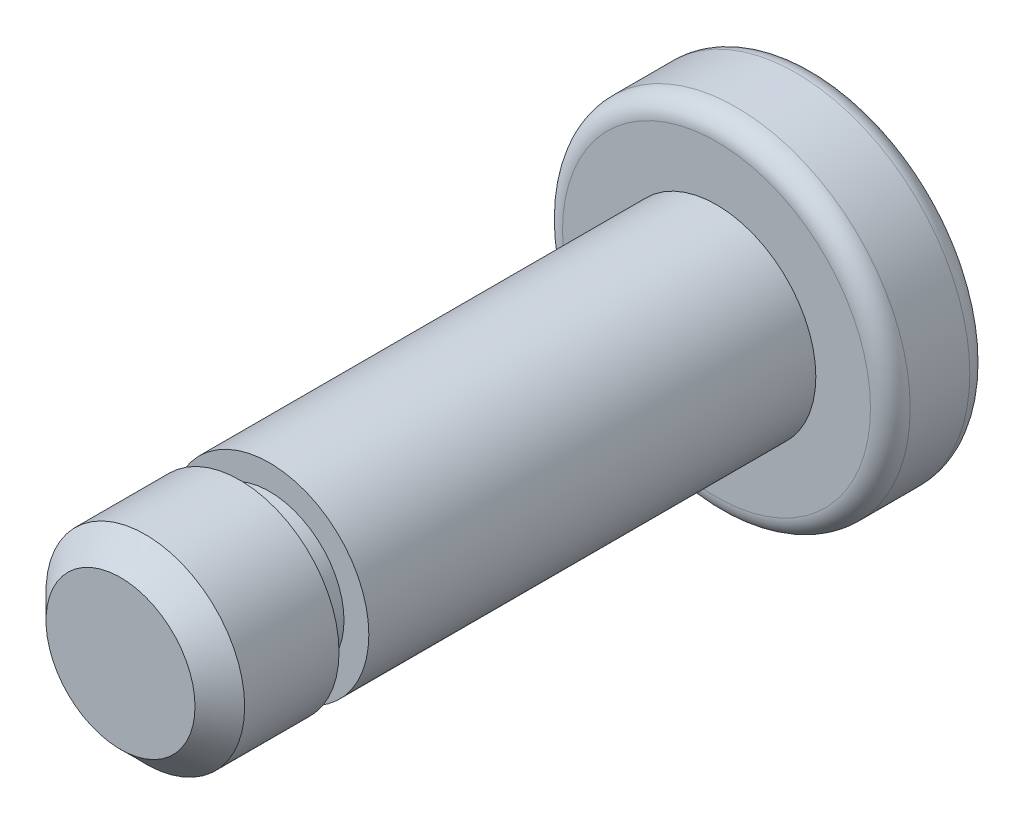
SolidWorks part; units mm, degrees
ref_plane "前视基准面" through (0, 0, 0) normal (0, 0, 1) x (1, 0, 0)
ref_plane "上视基准面" through (0, 0, 0) normal (0, 1, 0) x (1, 0, 0)
ref_plane "右视基准面" through (0, 0, 0) normal (1, 0, 0) x (0, 0, -1)
sketch "草图1" plane through (0, 0, 0) normal (0, 0, 1) x (1, 0, 0)
  circle A0 centre (0, 0) radius 3.5
  dimension "D1" = 7
extrude "凸台-拉伸1" add sketch "草图1" along normal blind 2
sketch "草图2" plane through (0, 0, 2) normal (0, 0, 1) x (1, 0, 0)
  circle A0 centre (0, 0) radius 2
  dimension "D1" = 4
extrude "凸台-拉伸2" add sketch "草图2" along normal blind 12
sketch "草图3" plane through (0, 0, 14) normal (0, 0, 1) x (1, 0, 0)
  circle A0 centre (0, 0) radius 2
  circle A1 centre (0, 0) radius 1.5
  dimension "D1" = 3
  dimension "D2" = 4
extrude "切除-拉伸1" cut sketch "草图3" along normal blind 0.6 from offset 3 offset against normal yes
chamfer "倒角1" distance 0.5 angle 45 1 edges at (2, 0, 14)
fillet "圆角1" radius 0.4 2 edges at (3.5, 0, 0) (3.5, 0, 2)
